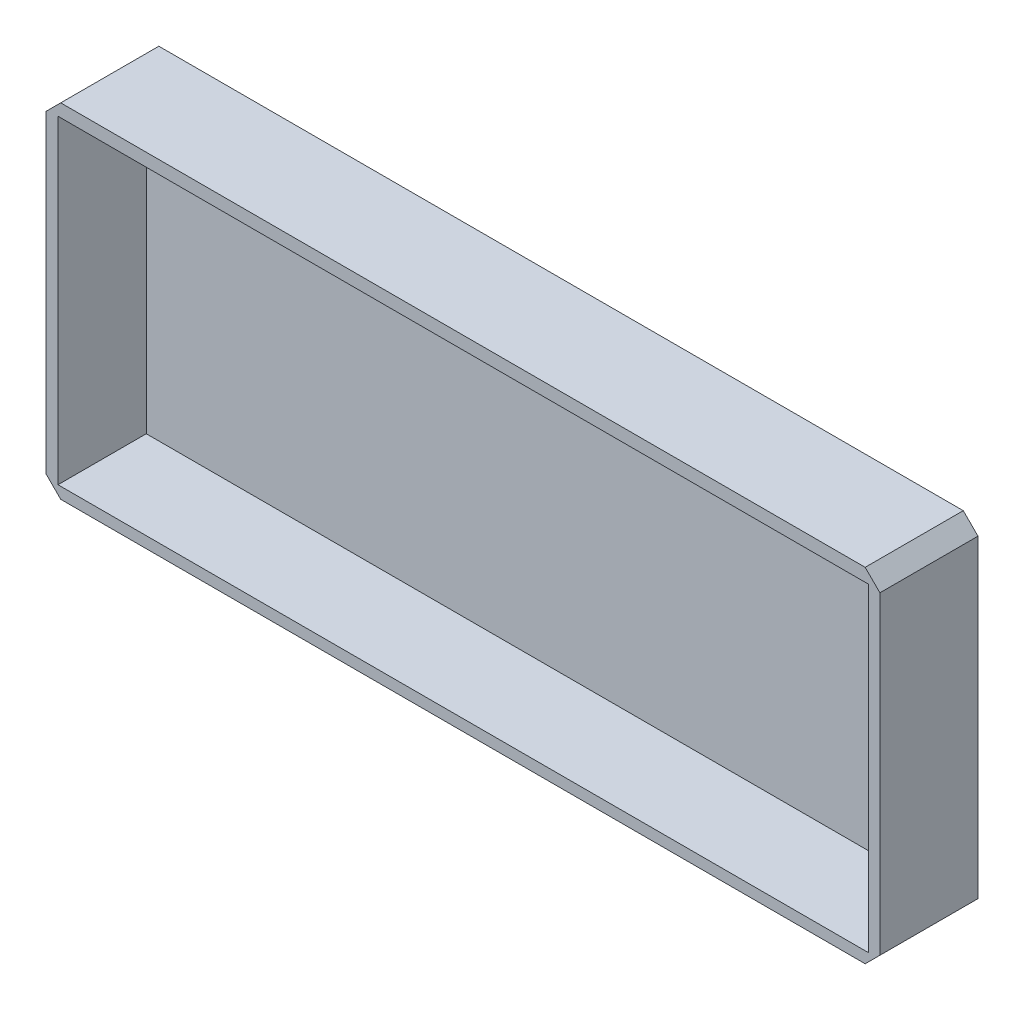
SolidWorks part; units mm, degrees
ref_plane "Front Plane" through (0, 0, 0) normal (0, 0, 1) x (1, 0, 0)
ref_plane "Top Plane" through (0, 0, 0) normal (0, 1, 0) x (1, 0, 0)
ref_plane "Right Plane" through (0, 0, 0) normal (1, 0, 0) x (0, 0, -1)
sketch "Sketch1" plane through (0, 0, 0) normal (0, 0, 1) x (1, 0, 0)
  line L1 (0, 0) -> (170, 0)
  line L2 (0, 0) -> (0, -70)
  line L3 (0, -70) -> (170, -70)
  line L4 (170, 0) -> (170, -70)
extrude "Boss-Extrude1" add sketch "Sketch1" along normal blind 20
sketch "Sketch2" plane through (0, 0, 20) normal (0, 0, 1) x (1, 0, 0)
  line L1 (2.4449, -2.6404) -> (167.725, -2.6404)
  line L2 (2.4449, -2.6404) -> (2.4449, -67.6993)
  line L3 (2.4449, -67.6993) -> (167.725, -67.6993)
  line L4 (167.725, -2.6404) -> (167.725, -67.6993)
extrude "Cut-Extrude1" cut sketch "Sketch2" against normal blind 18
chamfer "Chamfer1" distance 3 angle 45 4 edges at (170, -70, 10) (170, 0, 10) (0, 0, 10) (0, -70, 10)
